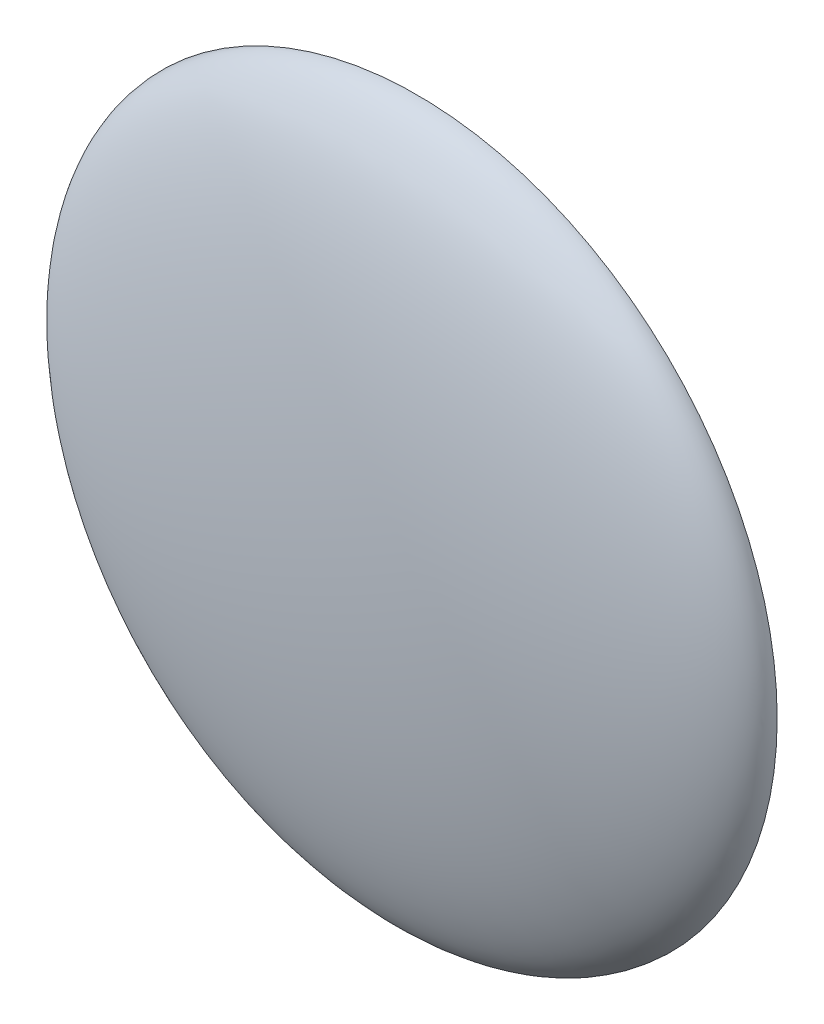
SolidWorks part; units mm, degrees
ref_plane "Front Plane" through (0, 0, 0) normal (0, 0, 1) x (1, 0, 0)
ref_plane "Top Plane" through (0, 0, 0) normal (0, 1, 0) x (1, 0, 0)
ref_plane "Right Plane" through (0, 0, 0) normal (1, 0, 0) x (0, 0, -1)
sketch "Sketch1" plane through (0, 0, 0) normal (0, 1, 0) x (1, 0, 0)
  line L0 (0, 0) -> (0, 130)
  line L1 (0, 130) -> (-540, 130)
  ellipse E0 centre (0, 130) end of major axis (-540, 130) minor radius 130 (0, 0) -> (-540, 130) cw
  dimension "D1" = 540
  dimension "D2" = 130
revolve "Revolve1" add sketch "Sketch1" angle 360 about L0
